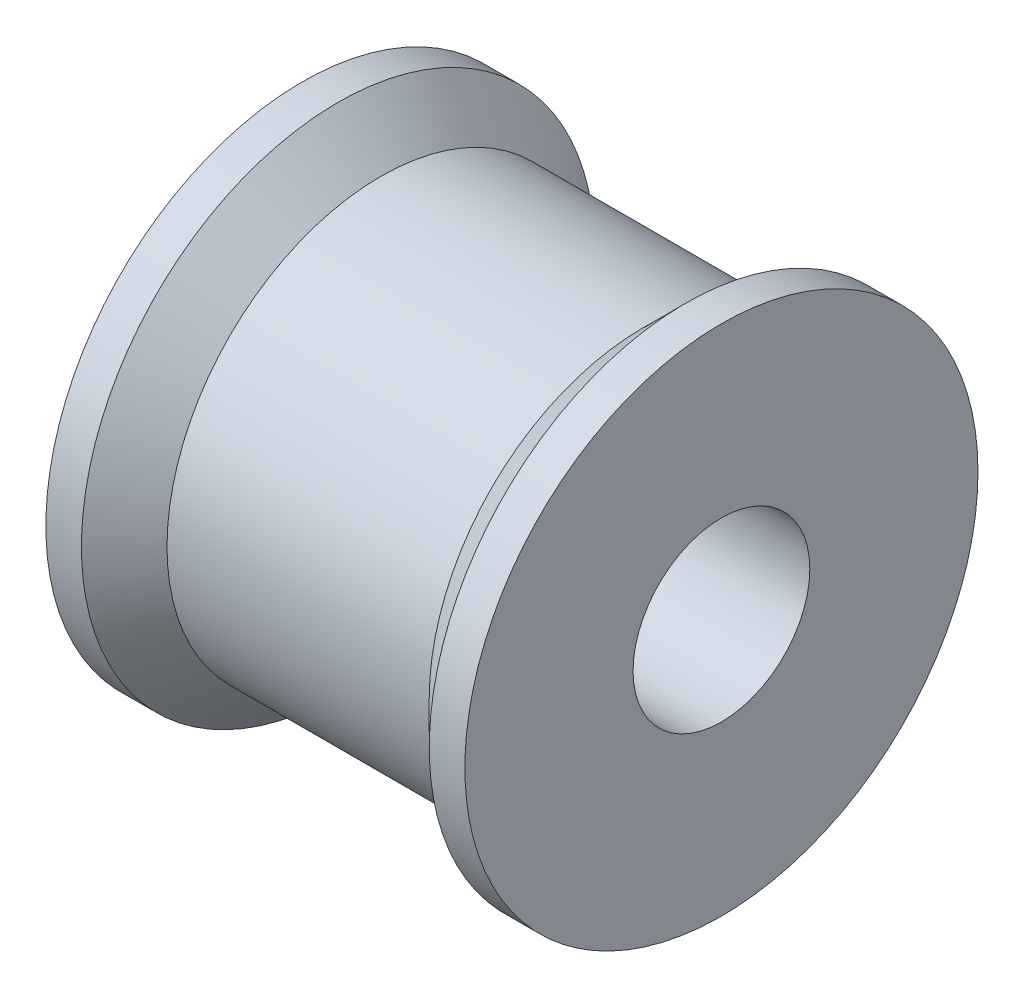
SolidWorks part; units mm, degrees
ref_plane "Front Plane" through (0, 0, 0) normal (0, 0, 1) x (1, 0, 0)
ref_plane "Top Plane" through (0, 0, 0) normal (0, 1, 0) x (1, 0, 0)
ref_plane "Right Plane" through (0, 0, 0) normal (1, 0, 0) x (0, 0, -1)
sketch "Sketch2" plane through (0, 0, 0) normal (0, 1, 0) x (1, 0, 0)
  line L0 (-7.35, 9) -> (-6.1, 9)
  line L1 (-6.1, 9) -> (-4.6, 7.5)
  line L2 (-4.6, 7.5) -> (4.6, 7.5)
  line L3 (4.6, 7.5) -> (6.1, 9)
  line L4 (6.1, 9) -> (7.35, 9)
  line L5 (7.35, 9) -> (7.35, 0)
  line L6 (-7.35, 9) -> (-7.35, 0)
  line L7 (-54.6936, 0) -> (47.2254, 0) construction
  line L8 (0, -23.2469) -> (0, 34.557) construction
  line L9 (7.35, 0) -> (-7.35, 0)
  point P16 (0, 7.5)
  dimension "D1" = 9
  dimension "D2" = 2.75
  dimension "D3" = 9.2
  dimension "D4" = 7.5
revolve "Revolve1" add sketch "Sketch2" angle 360 about L9
sketch "Sketch3" plane through (-7.35, 0, 0) normal (-1, 0, 0) x (0, 0, 1)
  circle A0 centre (0, 0) radius 3.1
  dimension "D1" = 6.2
extrude "Cut-Extrude1" cut sketch "Sketch3" against normal up to surface (14.7 mm away) up to face at (7.35, 0, -9)
